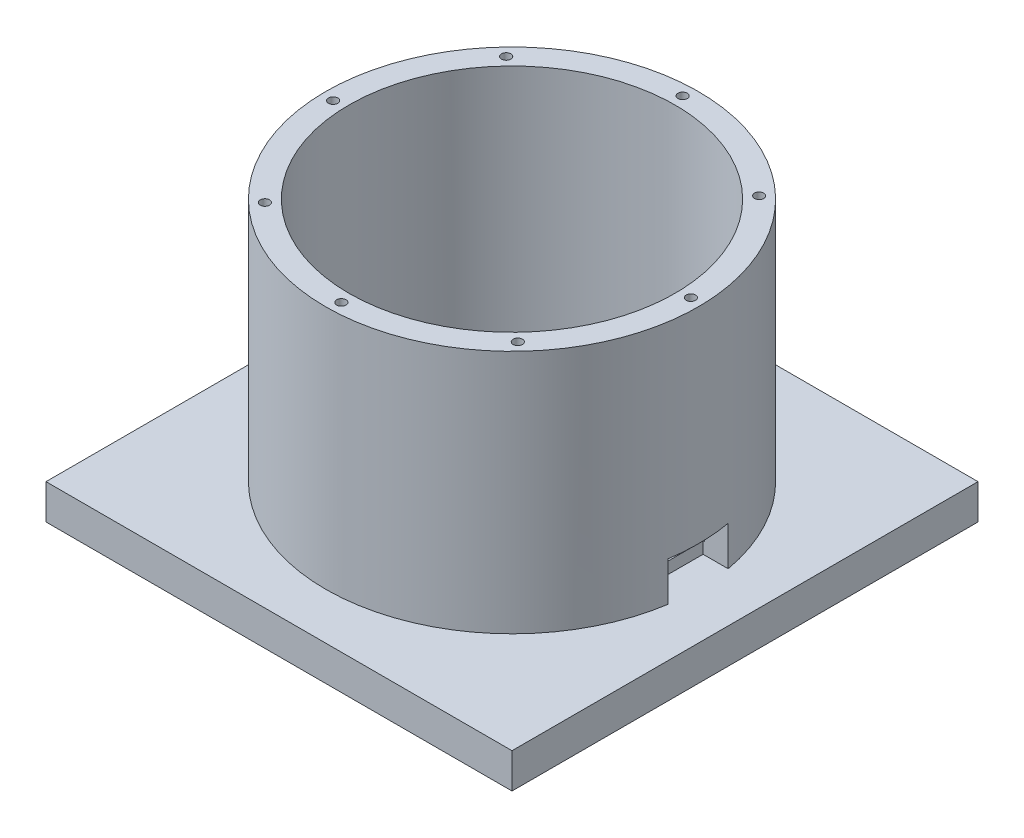
SolidWorks part; units mm, degrees
ref_plane "Alzado" through (0, 0, 0) normal (0, 0, 1) x (1, 0, 0)
ref_plane "Planta" through (0, 0, 0) normal (0, 1, 0) x (1, 0, 0)
ref_plane "Vista lateral" through (0, 0, 0) normal (1, 0, 0) x (0, 0, -1)
sketch "Croquis1" plane through (0, 0, 0) normal (0, 1, 0) x (1, 0, 0)
  circle A0 centre (0, 0) radius 80
  dimension "D1" = 160
extrude "Saliente-Extruir1" add sketch "Croquis1" along normal blind 5
sketch "Croquis2" plane through (0, 5, 0) normal (0, 1, 0) x (1, 0, 0)
  circle A0 centre (0, 0) radius 80
  circle A1 centre (0, 0) radius 70
  dimension "D1" = 10
extrude "Saliente-Extruir2" add sketch "Croquis2" along normal blind 100
sketch "Croquis3" plane through (0, 5, 0) normal (0, 1, 0) x (1, 0, 0)
  circle A0 centre (0, 0) radius 12.15
  circle A1 centre (0, 0) radius 16.15
  circle A2 centre (40, 0) radius 12.65
  circle A3 centre (40, 0) radius 17.65
  dimension "D1" = 4
  dimension "D2" = 24.3
  dimension "D4" = 25.3
  dimension "D5" = 5
  dimension "D3" = 40
extrude "Saliente-Extruir3" add sketch "Croquis3" along normal blind 8
sketch "Croquis5" plane through (0, 13, 0) normal (0, 1, 0) x (1, 0, 0)
  line L0 (50.236, 7.4328) -> (56.0086, 7.4328)
  line L1 (50.8118, -6.5672) -> (56.3828, -6.5672)
  arc A0 (56.0086, 7.4328) -> (56.3828, -6.5672) centre (40, 0) ccw
  arc A1 (50.236, 7.4328) -> (50.8118, -6.5672) centre (40, 0) ccw
  dimension "14" = 14
extrude "Saliente-Extruir4" add sketch "Croquis5" along normal blind 50
sketch "Croquis6" plane through (0, 0, 0) normal (0, -1, 0) x (1, 0, 0)
  line L1 (-100, 100) -> (100, 100)
  line L2 (-100, 100) -> (-100, -100)
  line L3 (-100, -100) -> (100, -100)
  line L4 (100, 100) -> (100, -100)
  dimension "D1" = 200
  dimension "D2" = 200
  dimension "D3" = 100
  dimension "D4" = 100
extrude "Saliente-Extruir5" add sketch "Croquis6" along normal blind 15
sketch "Croquis8" plane through (100, 0, 0) normal (1, 0, 0) x (0, 0, -1)
  line L0 (124.2518, 0) -> (-124.2518, 0) construction
  line L1 (-12.1894, 0) -> (14.0029, 0)
  line L2 (-12.1894, 0) -> (-12.1894, 16.9084)
  line L3 (-12.1894, 16.9084) -> (14.0029, 16.9084)
  line L4 (14.0029, 0) -> (14.0029, 16.9084)
extrude "Cortar-Extruir1" cut sketch "Croquis8" against normal blind 32
sketch "Croquis9" plane through (0, 105, 0) normal (0, 1, 0) x (1, 0, 0)
  circle A0 centre (-1.7651, 75) radius 2
  circle A1 centre (-1.7651, 75) radius 2
  circle A2 centre (-1.7651, 75) radius 2
  circle A3 centre (-1.7651, 75) radius 2
  circle A4 centre (-1.7651, 75) radius 2
  circle A5 centre (-1.7651, 75) radius 2
  circle A6 centre (-1.7651, 75) radius 2
  circle A7 centre (-1.7651, 75) radius 2
  circle A8 centre (51.7849, 54.2811) radius 2
  circle A9 centre (75, 1.7651) radius 2
  circle A10 centre (54.2811, -51.7849) radius 2
  circle A11 centre (1.7651, -75) radius 2
  circle A12 centre (-51.7849, -54.2811) radius 2
  circle A13 centre (-75, -1.7651) radius 2
  circle A14 centre (-54.2811, 51.7849) radius 2
  point P33 (0, 0)
  dimension "D2" = 4
  dimension "D1" = 75
  dimension "D3" = 8
  dimension "D4" = 8
extrude "Cortar-Extruir2" cut sketch "Croquis9" against normal blind 10 contours A14 | A0 | A12 | A9 | A13 | A11 | A10 | A8
